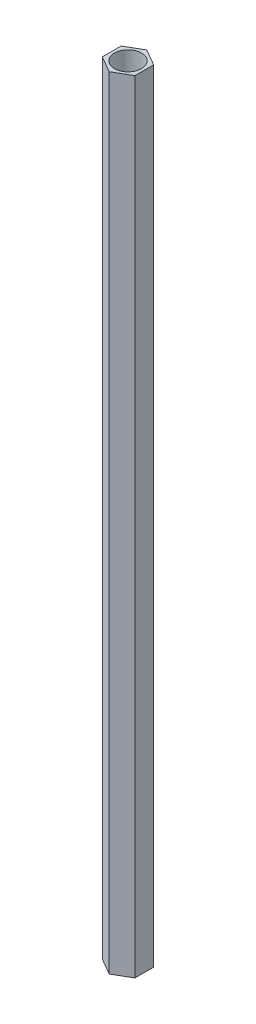
SolidWorks part; units mm, degrees
ref_plane "Front Plane" through (0, 0, 0) normal (0, 0, 1) x (1, 0, 0)
ref_plane "Top Plane" through (0, 0, 0) normal (0, 1, 0) x (1, 0, 0)
ref_plane "Right Plane" through (0, 0, 0) normal (1, 0, 0) x (0, 0, -1)
sketch "Sketch1" plane through (0, 0, 0) normal (0, 1, 0) x (1, 0, 0)
  line L1 (0, 1.7321) -> (-1.5, 0.866)
  line L2 (-1.5, 0.866) -> (-1.5, -0.866)
  line L3 (-1.5, -0.866) -> (0, -1.7321)
  line L4 (0, -1.7321) -> (1.5, -0.866)
  line L5 (1.5, -0.866) -> (1.5, 0.866)
  line L6 (1.5, 0.866) -> (0, 1.7321)
  circle A0 centre (0, 0) radius 1.5 construction
  dimension "D1" = 3
extrude "Boss-Extrude1" add sketch "Sketch1" along normal blind 72
hole_wizard "M3x0.5 Tapped Hole1" positions "Sketch2" profile "Sketch3" tap size "M3x0.5" standard "ANSI Metric"
sketch "Sketch2" plane through (0, 72, 0) normal (0, 1, 0) x (1, 0, 0)
  point P0 (0, 0)
sketch "Sketch3" plane through (0, 72, 0) normal (1, 0, 0) x (0, 0, 1)
  line L0 (0, 0) -> (0, 10.7511)
  line L1 (0, 10.7511) -> (1.25, 10)
  line L2 (1.25, 10) -> (1.25, 0)
  line L5 (1.25, 0) -> (0, 0)
  line L10 (0, 10.7511) -> (-1.25, 10) construction
  line L11 (0, -6.35) -> (0, 107.95) construction
  dimension "Tap Drill Dia." = 2.5
  dimension "Tap Drill Depth" = 10
  dimension "Drill Angle" = 118
hole_wizard "M3x0.5 Tapped Hole2" positions "Sketch4" profile "Sketch5" tap size "M3x0.5" standard "ANSI Metric"
sketch "Sketch4" plane through (0, 0, 0) normal (0, -1, 0) x (-1, 0, 0)
  point P0 (0, 0)
sketch "Sketch5" plane through (0, 0, 0) normal (1, 0, 0) x (0, 0, -1)
  line L0 (0, 0) -> (0, 10.7511)
  line L1 (0, 10.7511) -> (1.25, 10)
  line L2 (1.25, 10) -> (1.25, 0)
  line L5 (1.25, 0) -> (0, 0)
  line L10 (0, 10.7511) -> (-1.25, 10) construction
  line L11 (0, -6.35) -> (0, 107.95) construction
  dimension "Tap Drill Dia." = 2.5
  dimension "Tap Drill Depth" = 10
  dimension "Drill Angle" = 118
